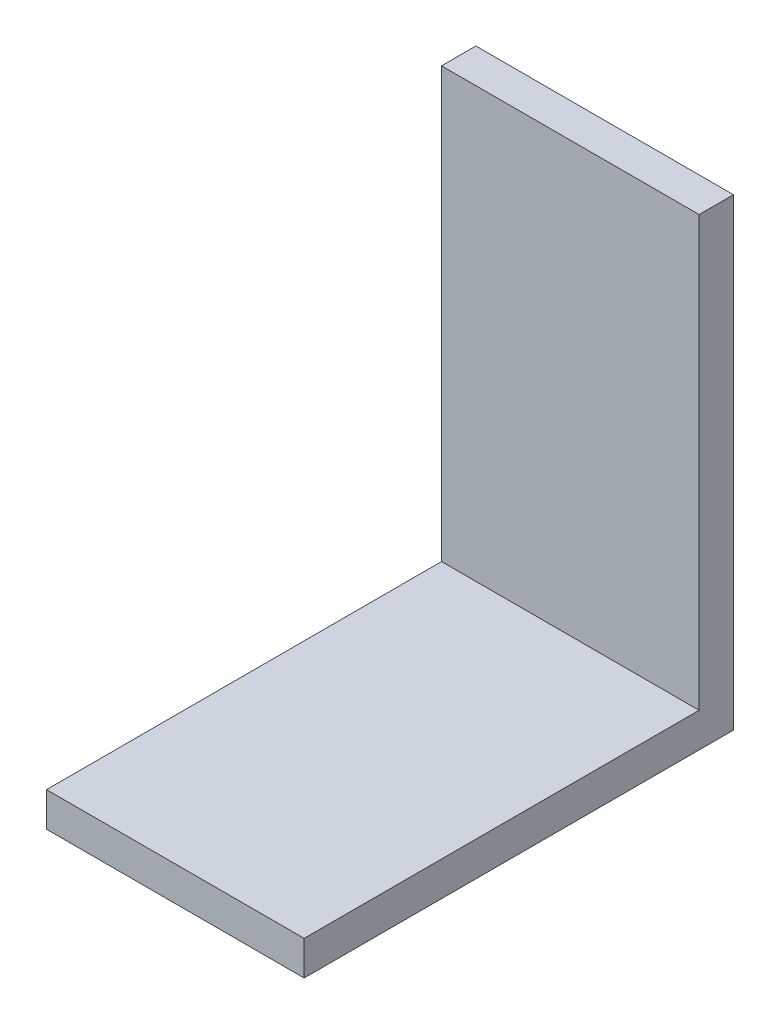
SolidWorks part; units mm, degrees
ref_plane "Front Plane" through (0, 0, 0) normal (0, 0, 1) x (1, 0, 0)
ref_plane "Top Plane" through (0, 0, 0) normal (0, 1, 0) x (1, 0, 0)
ref_plane "Right Plane" through (0, 0, 0) normal (1, 0, 0) x (0, 0, -1)
sketch "Sketch1" plane through (0, 0, 0) normal (0, 1, 0) x (1, 0, 0)
  line L1 (-7.5, -12.5) -> (7.5, -12.5)
  line L2 (-7.5, -12.5) -> (-7.5, 12.5)
  line L3 (-7.5, 12.5) -> (7.5, 12.5)
  line L4 (7.5, -12.5) -> (7.5, 12.5)
  line L5 (-7.5, -12.5) -> (7.5, 12.5) construction
  line L6 (-7.5, 12.5) -> (7.5, -12.5) construction
  point P0 (0, 0)
  dimension "D1" = 25
  dimension "D2" = 15
extrude "Boss-Extrude1" add sketch "Sketch1" along normal blind 2
sketch "Sketch2" plane through (0, 2, 0) normal (0, 1, 0) x (1, 0, 0)
  line L0 (0, -55) -> (0, 55) construction
  line L1 (-7.5, 10.5) -> (7.5, 10.5)
  line L2 (-7.5, 10.5) -> (-7.5, 12.5)
  line L3 (-7.5, 12.5) -> (7.5, 12.5)
  line L4 (7.5, 10.5) -> (7.5, 12.5)
  line L5 (-7.5, 10.5) -> (7.5, 12.5) construction
  line L6 (-7.5, 12.5) -> (7.5, 10.5) construction
  point P0 (0, 11.5)
  dimension "D1" = 2
extrude "Boss-Extrude2" add sketch "Sketch2" along normal blind 25
